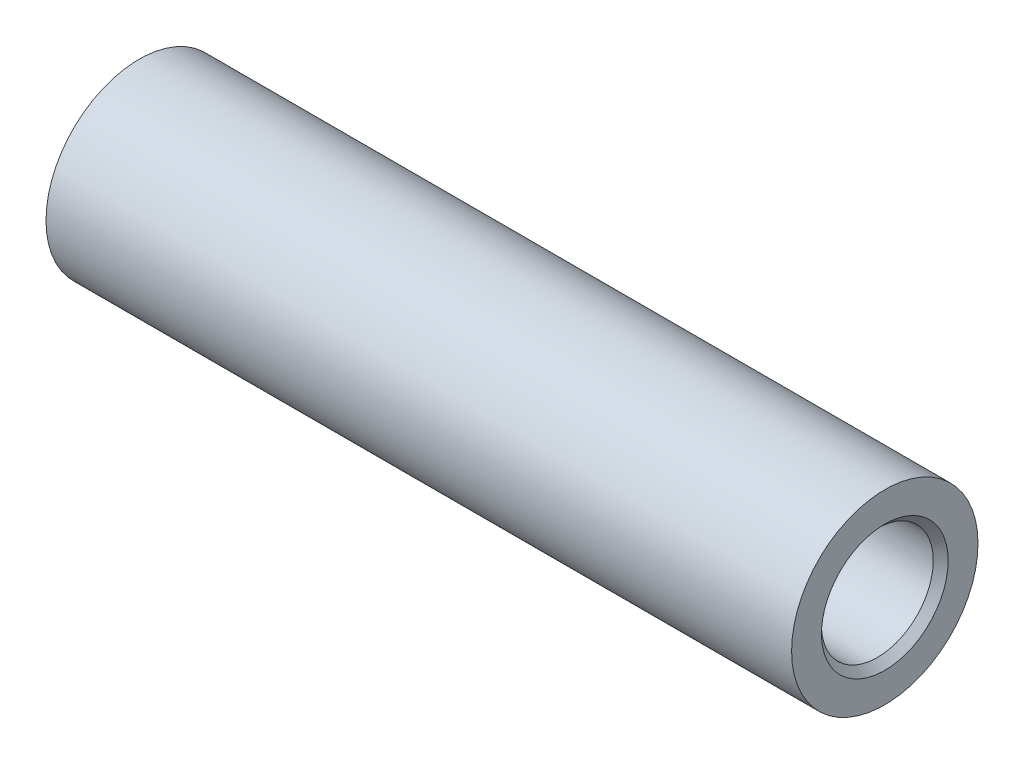
SolidWorks part; units mm, degrees
ref_plane "前视基准面" through (0, 0, 0) normal (0, 0, 1) x (1, 0, 0)
ref_plane "上视基准面" through (0, 0, 0) normal (0, 1, 0) x (1, 0, 0)
ref_plane "右视基准面" through (0, 0, 0) normal (1, 0, 0) x (0, 0, -1)
other "Configuration Table"
sketch "草图1" plane through (0, 0, 0) normal (1, 0, 0) x (0, 0, -1)
  circle A0 centre (0, 0) radius 5
  dimension "D1" = 10
extrude "凸台-拉伸1" add sketch "草图1" along normal blind 19 and the other way blind 21
sketch "草图3" plane through (19, 0, 0) normal (1, 0, 0) x (0, 0, -1)
  circle A0 centre (0, 0) radius 3
  dimension "D1" = 6
extrude "切除-拉伸1" cut sketch "草图3" against normal blind 17
sketch "草图4" plane through (-21, 0, 0) normal (-1, 0, 0) x (0, 0, 1)
  circle A0 centre (0, 0) radius 4
  dimension "D1" = 8
extrude "切除-拉伸2" cut sketch "草图4" against normal blind 21
sketch "草图5" plane through (2, 0, 0) normal (1, 0, 0) x (0, 0, -1)
  line L0 (-1.6583, 2.5) -> (1.6583, 2.5)
  circle A0 centre (0, 0) radius 3 construction
  arc A1 (1.6583, 2.5) -> (-1.6583, 2.5) centre (0, 0) ccw
  arc A2 (-1.6583, 2.5) -> (1.6583, 2.5) centre (0, 0) ccw construction
  dimension "D1" = 2.5
extrude "凸台-拉伸2" add sketch "草图5" along normal blind 12 separate body
sketch "草图6" plane through (0, 0, 0) normal (-1, 0, 0) x (0, 0, 1)
  line L0 (-1.8995, 3.5202) -> (1.9732, 3.4794)
  circle A0 centre (0, 0) radius 4 construction
  arc A1 (1.9732, 3.4794) -> (-1.8995, 3.5202) centre (0, 0) ccw
  arc A2 (-1.8995, 3.5202) -> (1.9732, 3.4794) centre (0, 0) ccw construction
  dimension "D1" = 3.5
extrude "凸台-拉伸3" add sketch "草图6" along normal blind 15
chamfer "倒角1" distance 0.4 angle 45 2 edges at (19, 0, -3) (-21, 0, 4)
